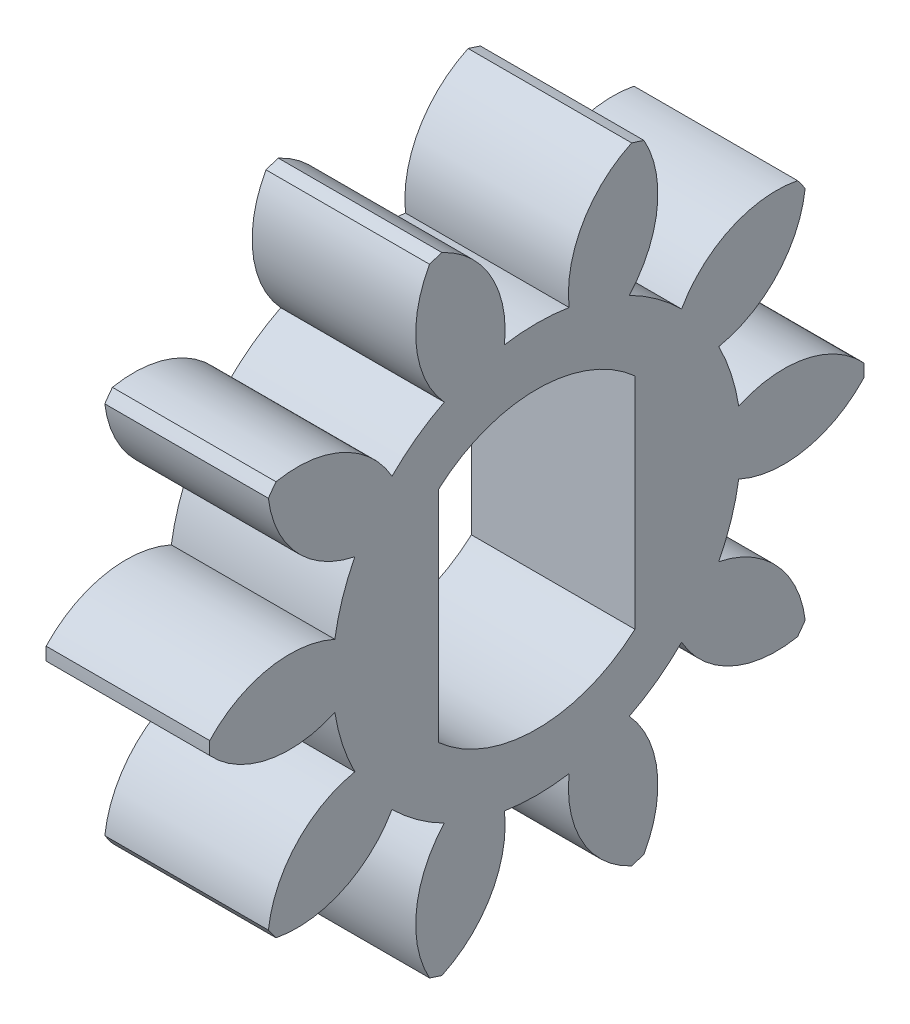
SolidWorks part; units mm, degrees
ref_plane "Plane1" through (0, 0, 0) normal (0, 0, 1) x (1, 0, 0)
ref_plane "Plane2" through (0, 0, 0) normal (0, 1, 0) x (1, 0, 0)
ref_plane "Plane3" through (0, 0, 0) normal (1, 0, 0) x (0, 0, -1)
sketch "HoldingSke" plane through (0, 0, 0) normal (0, 1, 0) x (1, 0, 0)
  line L0 (0, 0) -> (0.9848, -0.1736)
  line L1 (-15, 0) -> (100, 0) construction
  line L2 (0, 0) -> (-2.1039, 2.3779)
  line L3 (0, 0) -> (-11.863, 4.5341)
  line L4 (0, 0) -> (8.5048, 1.4996)
  line L5 (0, 0) -> (-46.8476, -17.4728)
  line L6 (0, 0) -> (-2.4869, -1.6779)
  line L7 (-2.1039, 2.3779) -> (8.6586, 51.2059)
  line L8 (-76.2, 54.61) -> (-75.2, 54.61)
  line L9 (-71.009, 38.7566) -> (-53.1078, 45.2721)
  line L10 (-76.2, 71.12) -> (104.1128, 71.12)
  line L11 (0, 0) -> (-3, 0)
  line L12 (-76.2, 101.6) -> (-76.162, 101.6)
  line L13 (24.9733, 27.94) -> (52.9518, 28.4284)
  line L14 (24.9733, 27.94) -> (24.9743, 27.94)
  line L15 (24.9733, 27.94) -> (100.4006, 29.5858)
  line L16 (-63.627, -1) -> (-12.827, -1)
  circle A0 centre (0, 0) radius 3
  circle A1 centre (0, 0) radius 3.749
  circle A2 centre (0, 0) radius 37.5
  circle A3 centre (0, 0) radius 3
  dimension "MHD" = 7.498
  dimension "Hub_dia" = 75
  dimension "Bore" = 6
  dimension "MBD" = 6
  dimension "Num_teeth" = 10
  dimension "Pitch" = 1
  dimension "Overall_len" = 50
  dimension "Show_teeth" = 10
  dimension "Thickness" = 3
  dimension "OAL" = 50.0001
  dimension "T_dim" = 1
  dimension "Ap" = 20
  dimension "H" = 19.05
  dimension "Pitch_radius" = 180.3128
  dimension "Width" = 3
  dimension "Backlash" = 0.038
  dimension "Addendum_fac" = 1
  dimension "Dedendum_fac" = 1.25
  dimension "Clearance_fac" = 0.25
  dimension "Dedendum_add" = 0.001
  dimension "Module" = 1
sketch "BasProSke" plane through (0, 0, 0) normal (0, 1, 0) x (1, 0, 0)
  line L0 (-10, 0) -> (60, 0) construction
  line L1 (0, 0) -> (0, 6)
  line L2 (0, 0) -> (3, 0)
  line L3 (3, 0) -> (3, 6)
  line L4 (3, 6) -> (0, 6)
  dimension "Thickness" = 3
  dimension "Diameter" = 12
revolve "Base-Revolve" add sketch "BasProSke" angle 360 about L0
sketch "TooCutSke" plane through (0, 0, 0) normal (1, 0, 0) x (0, 0, -1)
  line L1 (0, 0) -> (0, 107) construction
  line L2 (0, 0) -> (-0.8485, 4.9275) construction
  line L3 (0, 0) -> (-3.0584, 9.4126) construction
  line L4 (-0.8485, 4.9275) -> (-1.5292, 4.7063) construction
  arc A0 (0.5928, 3.7018) -> (-0.5928, 3.7018) centre (0, 0) ccw
  arc A1 (1.7758, 5.7578) -> (-1.7758, 5.7578) centre (0, 0) ccw
  circle A2 centre (0, 0) radius 5 construction
  circle A3 centre (0, 0) radius 4.6985 construction
  arc A4 (-0.5928, 3.7018) -> (-1.7758, 5.7578) centre (-2.5801, 3.9267) ccw
  arc A5 (1.7758, 5.7578) -> (0.5928, 3.7018) centre (2.5801, 3.9267) ccw
  dimension "Root_dia" = 7.498
  dimension "Overcut_dia" = 12.0508
  dimension "Pitch_dia" = 10
  dimension "Base_dia" = 9.3969
  dimension "Flank_rad" = 2
  dimension "Half_ang" = 18
  dimension "Half_CT" = 0.7157
extrude "ToothCut" cut sketch "TooCutSke" along normal through all
fillet "Breaks" [suppressed] radius 0.02
fillet "RootFillets" [suppressed] radius 0.251
pattern_circular "TeethCuts" count 10 over 360 about axis through (0, 0, 0) along (1, 0, 0) of "ToothCut", "RootFillets", "Breaks"
sketch "HubNeaOneSke" plane through (0, 0, 0) normal (-1, 0, 0) x (0, 0, 1)
  circle A0 centre (0, 0) radius 3.749
  dimension "Diameter" = 7.498
extrude "HubNearOne" [suppressed] add sketch "HubNeaOneSke" along normal blind 47.0001
sketch "HubNeaBotSke" plane through (0, 0, 0) normal (-1, 0, 0) x (0, 0, 1)
  circle A0 centre (0, 0) radius 3.749
  dimension "Diameter" = 7.498
extrude "HubNearBoth" [suppressed] add sketch "HubNeaBotSke" along normal blind 23.5
ref_plane "FarPln" through (3, 0, 0) normal (1, 0, 0) x (0, 0, -1)
sketch "HubFarSke" plane through (3, 0, 0) normal (1, 0, 0) x (0, 0, -1)
  circle A0 centre (0, 0) radius 3.749
  dimension "Diameter" = 7.498
extrude "HubFar" [suppressed] add sketch "HubFarSke" along normal blind 23.5
sketch "BorSke" plane through (0, 0, 0) normal (1, 0, 0) x (0, 0, -1)
  circle A0 centre (0, 0) radius 3
  dimension "Diameter" = 6
extrude "Bore" cut sketch "BorSke" along normal mid plane 100.0001
sketch "KeySke" plane through (0, 0, 0) normal (1, 0, 0) x (0, 0, -1)
  line L0 (-1, 0) -> (-1, 4)
  line L1 (-1, 4) -> (1, 4)
  line L2 (1, 4) -> (1, 0)
  line L3 (0, 0) -> (0, 34) construction
  line L4 (-1, 0) -> (1, 0)
  dimension "Offset" = 4
  dimension "Width" = 2
extrude "Keyway" [suppressed] cut sketch "KeySke" along normal mid plane 100.0001
pattern_circular "Keyway2" [suppressed] count 2 every 90 about axis through (-10, 0, 0) along (1, 0, 0)
sketch "Sketch1" plane through (3, 0, 0) normal (1, 0, 0) x (0, 0, -1)
  circle A0 centre (0, 0) radius 3 construction
  circle A1 centre (0, 0) radius 3
extrude "Boss-Extrude1" add sketch "Sketch1" against normal up to surface (3 mm away) up to face at (0, 0, -3)
sketch "Sketch2" plane through (3, 0, 0) normal (1, 0, 0) x (0, 0, -1)
  line L0 (-1.8, 2.0125) -> (-1.8, -2.0125)
  line L1 (1.8, 2.0125) -> (1.8, -2.0125)
  line L2 (-1.8, 0) -> (1.8, 0) construction
  circle A0 centre (0, 0) radius 2.7
  point P9 (0, 0)
  dimension "D1" = 5.4
  dimension "D2" = 3.6
extrude "Cut-Extrude1" cut sketch "Sketch2" against normal up to surface (3 mm away) contours L0 L2 L1 A0 | L2 L0 A0 L1 up to face at (0, 0, 0)
sketch "Sketch3" plane through (3, 0, 0) normal (1, 0, 0) x (0, 0, -1)
  circle A0 centre (0, 0) radius 3
  dimension "D1" = 6
extrude "Cut-Extrude2" cut sketch "Sketch3" against normal up to surface (3 mm away) up to face at (0, 0, 0)
sketch "Sketch4" plane through (3, 0, 0) normal (1, 0, 0) x (0, 0, -1)
  circle A0 centre (0, 0) radius 3 construction
  circle A1 centre (0, 0) radius 3
extrude "Boss-Extrude2" add sketch "Sketch4" against normal up to surface (3 mm away) up to face at (0, 0, -3)
sketch "Sketch5" plane through (3, 0, 0) normal (1, 0, 0) x (0, 0, -1)
  line L0 (-1.8, 2.0125) -> (-1.8, -2.0125)
  line L1 (1.8, 2.0125) -> (1.8, -2.0125)
  line L2 (-1.8, 0) -> (1.8, 0) construction
  circle A0 centre (0, 0) radius 2.7
  point P9 (0, 0)
  dimension "D1" = 5.4
  dimension "D2" = 3.6
extrude "Cut-Extrude3" cut sketch "Sketch5" against normal up to surface (3 mm away) contours L0 L2 L1 A0 | L2 L0 A0 L1 up to face at (0, 0, 0)
equation "' \"Module@HoldingSke\" = 6.35"
equation "' \"Num_teeth@HoldingSke\" = 12"
equation "' \"Ap@HoldingSke\" =  20"
equation "' \"Ap@HoldingSke\" = 20"
equation "' \"Width@HoldingSke\" = 0.5 * 25.4"
equation "' \"Hub_dia@HoldingSke\"= 1 * 25.4"
equation "' \"Hub_dia@HoldingSke\" = 1 * 25.4"
equation "' \"Overall_len@HoldingSke\" = 1.0 * 25.4"
equation "' \"Bore@HoldingSke\" = 0.75 * 25.4"
equation "' \"T_dim@HoldingSke\" = 0.1 * 25.4"
equation "' \"Width@KeySke\" = 0.25 * 25.4"
equation "' \"Show_teeth@HoldingSke\" = 13"
equation "' \"Backlash@HoldingSke\" = 0.009 * 25.4"
equation "' \"Addendum_fac@HoldingSke\" = 1.0"
equation "' \"Dedendum_fac@HoldingSke\" = 1.25"
equation "' \"Dedendum_add@HoldingSke\" = 0.00005 * 25.4"
equation "' \"Clearance_fac@HoldingSke\" = 0.25"
equation "\"Pitch@HoldingSke\" = 1 / \"Module@HoldingSke\""
equation "\"Overcut_dia@TooCutSke\" = (\"Num_teeth@HoldingSke\" + 2 * \"Addendum_fac@HoldingSke\") / \"Pitch@HoldingSke\" + 0.002 * 25.4"
equation "\"Pitch_dia@TooCutSke\" = \"Num_teeth@HoldingSke\" / \"Pitch@HoldingSke\""
equation "\"Base_dia@TooCutSke\" = \"Num_teeth@HoldingSke\" / \"Pitch@HoldingSke\" * cos((\"Ap@HoldingSke\"  * 3.14159265 / 180))"
equation "\"Root_dia@TooCutSke\" = (\"Num_teeth@HoldingSke\" + 2) / \"Pitch@HoldingSke\" - 2 * (\"Addendum_fac@HoldingSke\" + \"Dedendum_fac@HoldingSke\") / \"Pitch@HoldingSke\" - \"Dedendum_add@HoldingSke\" * 2"
equation "\"Half_ang@TooCutSke\" = 180 / \"Num_teeth@HoldingSke\""
equation "\"Half_CT@TooCutSke\" = \"Num_teeth@HoldingSke\" / \"Pitch@HoldingSke\" * sin((3.14159265 / 2 / \"Num_teeth@HoldingSke\")) / 2 - 7 * \"Backlash@HoldingSke\" / 4"
equation "\"Flank_rad@TooCutSke\" = \"Num_teeth@HoldingSke\" / \"Pitch@HoldingSke\" / 5"
equation "\"Radius@RootFillets\" = \"Clearance_fac@HoldingSke\" / \"Pitch@HoldingSke\" + \"Dedendum_add@HoldingSke\""
equation "\"Break_rad@Breaks\" = 0.02 / \"Pitch@HoldingSke\""
equation "\"Thickness@HoldingSke\" = \"Width@HoldingSke\""
equation "\"OAL@HoldingSke\" = \"Thickness@HoldingSke\""
equation "\"MHD@HoldingSke\" = (\"Num_teeth@HoldingSke\" + 2) / \"Pitch@HoldingSke\" - 2 * (\"Addendum_fac@HoldingSke\" + \"Dedendum_fac@HoldingSke\")  / \"Pitch@HoldingSke\" - \"Dedendum_add@HoldingSke\" * 2"
equation "\"MBD@HoldingSke\" = (\"Num_teeth@HoldingSke\" + 2) / \"Pitch@HoldingSke\" - 2 * (\"Addendum_fac@HoldingSke\" + \"Dedendum_fac@HoldingSke\")  / \"Pitch@HoldingSke\" - \"Dedendum_add@HoldingSke\" * 2 - 0.002 * 25.4"
equation "\"MHD@HoldingSke\" = ((sgn( \"MHD@HoldingSke\" - \"Hub_dia@HoldingSke\" )-1)*( \"MHD@HoldingSke\" - \"Hub_dia@HoldingSke\" ))/-2+ \"Hub_dia@HoldingSke\""
equation "\"MBD@HoldingSke\" = ((sgn( \"MBD@HoldingSke\" - \"Bore@HoldingSke\" )-1)*( \"MBD@HoldingSke\" - \"Bore@HoldingSke\" ))/-2+ \"Bore@HoldingSke\""
equation "\"OAL@HoldingSke\" = ((sgn( \"OAL@HoldingSke\" - \"Overall_len@HoldingSke\" )+1)*( \"OAL@HoldingSke\" - \"Overall_len@HoldingSke\" ))/2 + \"Overall_len@HoldingSke\" + 0.000002 * 25.4"
equation "\"Num_teeth@TeethCuts\" = int( \"Show_teeth@HoldingSke\" ) + 1"
equation "\"Num_teeth@TeethCuts\" = ((sgn( \"Num_teeth@TeethCuts\" - \"Num_teeth@HoldingSke\" )-1)*( \"Num_teeth@TeethCuts\" - \"Num_teeth@HoldingSke\" ))/-2+ \"Num_teeth@HoldingSke\""
equation "\"Num_teeth@TeethCuts\" = ((sgn( \"Num_teeth@TeethCuts\" - 2.0)+1)*( \"Num_teeth@TeethCuts\" - 2.0))/2 +2.0"
equation "\"Angle@TeethCuts\" = 360.0 / \"Num_teeth@HoldingSke\""
equation "\"Diameter@BasProSke\" = (\"Num_teeth@HoldingSke\" + 2 * \"Addendum_fac@HoldingSke\") / \"Pitch@HoldingSke\""
equation "\"Thickness@BasProSke\"  = \"Thickness@HoldingSke\""
equation "' \"Fillet_rad@BasProSke\" =  \"Thickness@HoldingSke\" * 0.05"
equation "' \"Fillet_rad@BasProSke\" = \"Thickness@HoldingSke\" * 0.05"
equation "\"MHD@HoldingSke\" = ((sgn( \"MHD@HoldingSke\" - \"Root_dia@TooCutSke\" )-1)*( \"MHD@HoldingSke\" - \"Root_dia@TooCutSke\" ))/-2+ \"Root_dia@TooCutSke\""
equation "\"Diameter@HubNeaOneSke\" = \"MHD@HoldingSke\""
equation "\"Length@HubNearOne\" = \"OAL@HoldingSke\" - \"Thickness@BasProSke\""
equation "\"Diameter@HubNeaBotSke\" = \"MHD@HoldingSke\""
equation "\"Length@HubNearBoth\" = ( \"OAL@HoldingSke\" - \"Thickness@BasProSke\" ) / 2.0"
equation "\"Thickness@FarPln\" = \"Thickness@BasProSke\""
equation "\"Diameter@HubFarSke\" = \"MHD@HoldingSke\""
equation "\"Length@HubFar\" = ( \"OAL@HoldingSke\" - \"Thickness@BasProSke\" ) / 2.0"
equation "\"Diameter@BorSke\" = \"MBD@HoldingSke\""
equation "\"D1@Bore\" = \"OAL@HoldingSke\" * 2.0"
equation "\"D1@Keyway\" = \"OAL@HoldingSke\" * 2.0"
equation "\"Offset@KeySke\" = \"T_dim@HoldingSke\" + \"MBD@HoldingSke\" / 2.0"
